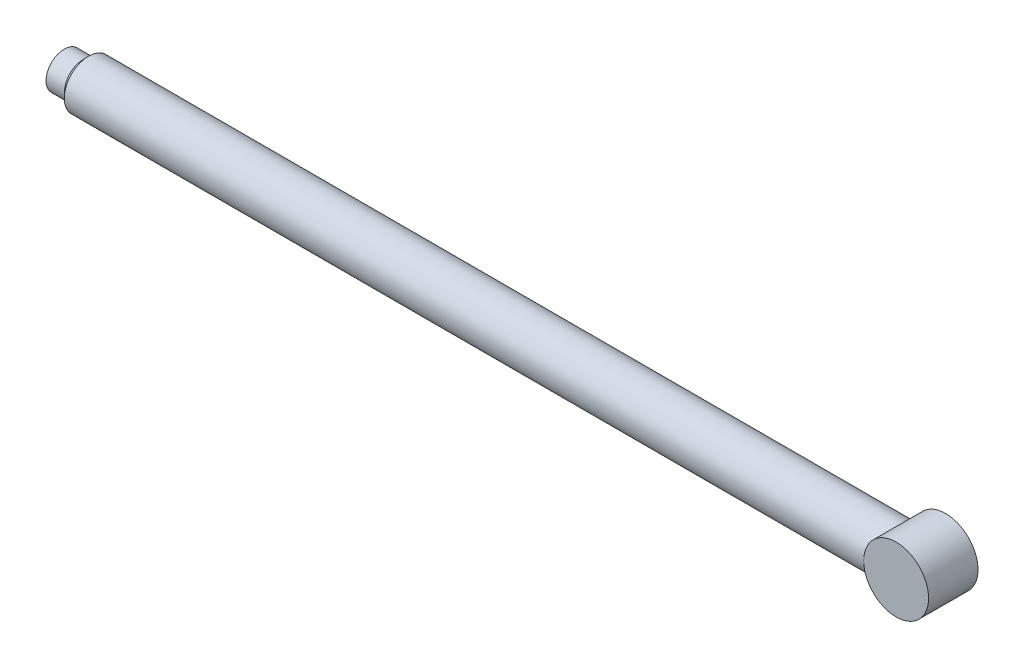
SolidWorks part; units mm, degrees
ref_plane "Front Plane" through (0, 0, 0) normal (0, 0, 1) x (1, 0, 0)
ref_plane "Top Plane" through (0, 0, 0) normal (0, 1, 0) x (1, 0, 0)
ref_plane "Right Plane" through (0, 0, 0) normal (1, 0, 0) x (0, 0, -1)
sketch "Sketch2" plane through (0, 0, 0) normal (1, 0, 0) x (0, 0, -1)
  circle A0 centre (0, 0) radius 150
  circle A1 centre (0, 0) radius 62.5
  dimension "D1" = 300
  dimension "D2" = 125
extrude "Boss-Extrude1" add sketch "Sketch2" along normal blind 5000
sketch "Sketch3" plane through (0, 0, 0) normal (-1, 0, 0) x (0, 0, 1)
  circle A0 centre (0, 0) radius 112.5
  circle A1 centre (0, 0) radius 92.5
  dimension "D1" = 225
  dimension "D2" = 185
extrude "Boss-Extrude2" add sketch "Sketch3" along normal blind 150
sketch "Sketch4" plane through (0, 0, 0) normal (0, 0, 1) x (1, 0, 0)
  circle A0 centre (5132.8297, 0) radius 200
  circle A1 centre (5132.8297, 0) radius 150
  point P2 (5131.7982, -3.8475)
  point P3 (5132.8297, 0)
  dimension "D1" = 400
  dimension "D2" = 300
extrude "Boss-Extrude9" add sketch "Sketch4" along normal through all and the other way through all separate body
sketch "Sketch5" plane through (0, 0, 150) normal (0, 0, 1) x (1, 0, 0)
  circle A0 centre (5132.8297, 0) radius 150
  dimension "D1" = 300
extrude "Cut-Extrude1" cut sketch "Sketch5" against normal blind 175
sketch "Sketch6" plane through (0, 0, 0) normal (-1, 0, 0) x (0, 0, 1)
  circle A0 centre (0, 0) radius 50
  dimension "D1" = 100
extrude "Cut-Extrude2" cut sketch "Sketch6" against normal blind 5024
sketch "Sketch7" plane through (0, 0, 0) normal (0, 0, 1) x (1, 0, 0)
  line L0 (0, 112.5) -> (0, 150)
  line L4 (-224.7945, 0) -> (133.1421, 0) construction
  line L5 (0, 112.5) -> (-35.5102, 112.5)
  line L6 (0, 112.5) -> (-150, 112.5) construction
  line L7 (-35.5102, 112.5) -> (0, 150)
  point P4 (-35.5102, 112.5)
revolve "Revolve1" add sketch "Sketch7" angle 360 about L4
sketch "Sketch9" plane through (0, 0, 150) normal (0, 0, 1) x (1, 0, 0)
  circle A0 centre (5132.8297, 0) radius 200
  point P3 (5050.1346, 0)
  point P4 (5050.1346, 0)
  dimension "D1" = 400
extrude "Boss-Extrude10" add sketch "Sketch9" along normal blind 5 and the other way blind 5
sketch "Sketch10" plane through (0, 0, -150) normal (0, 0, -1) x (-1, 0, 0)
  circle A0 centre (-5132.8297, 0) radius 150
  dimension "D1" = 300
extrude "Cut-Extrude3" cut sketch "Sketch10" against normal blind 202
